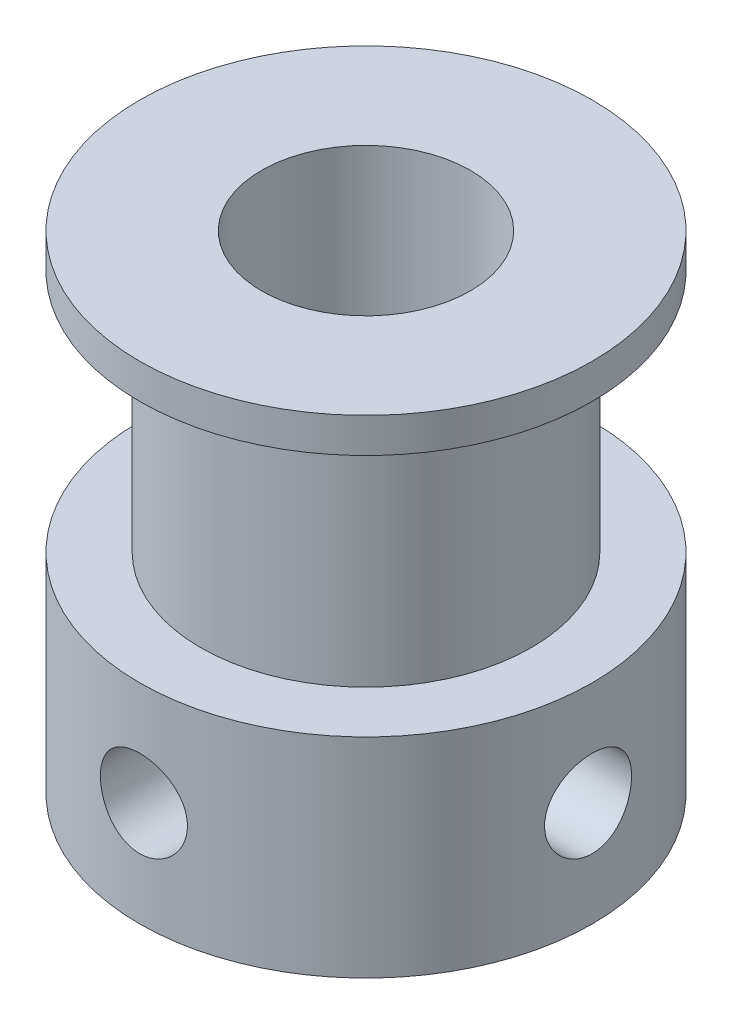
SolidWorks part; units mm, degrees
material "6063-O"
ref_plane "前视基准面" through (0, 0, 0) normal (0, 0, 1) x (1, 0, 0)
ref_plane "上视基准面" through (0, 0, 0) normal (0, 1, 0) x (1, 0, 0)
ref_plane "右视基准面" through (0, 0, 0) normal (1, 0, 0) x (0, 0, -1)
sketch "草图1" plane through (0, 0, 0) normal (0, 0, 1) x (1, 0, 0)
  line L0 (0, 0) -> (0, 14) construction
  line L1 (3, 0) -> (6.5, 0)
  line L2 (6.5, 0) -> (6.5, 6)
  line L3 (6.5, 6) -> (4.75, 6)
  line L4 (4.75, 6) -> (4.75, 13)
  line L5 (4.75, 13) -> (6.5, 13)
  line L6 (6.5, 13) -> (6.5, 14)
  line L7 (6.5, 14) -> (3, 14)
  line L8 (3, 14) -> (3, 0)
  dimension "D1" = 6
  dimension "D2" = 13
  dimension "D3" = 14
  dimension "D4" = 7
  dimension "D5" = 9.5
  dimension "D6" = 1
revolve "旋转1" add sketch "草图1" angle 360 about L0
hole_wizard "M3 螺纹孔1" positions "草图2" profile "草图3" tap size "M3" standard "GB"
sketch "草图2" plane through (0, 0, 0) normal (0, 0, 1) x (1, 0, 0)
  point P0 (0, 3)
  dimension "D1" = 3
sketch "草图3" plane through (0, 3, 0) normal (1, 0, 0) x (0, 1, 0)
  line L0 (0, 0) -> (0, 6.5)
  line L1 (0, 6.5) -> (1.25, 6.5)
  line L2 (1.25, 6.5) -> (1.25, 0.275)
  line L3 (1.25, 0.275) -> (1.525, 0)
  line L5 (1.525, 0) -> (0, 0)
  line L6 (-1.25, 0.275) -> (-1.525, 0) construction
  line L11 (0, -6.35) -> (0, 107.95) construction
  dimension "通孔螺纹孔钻头直径" = 2.5
  dimension "通孔螺纹孔钻头深度" = 6.5
  dimension "近端锥形沉头孔直径" = 3.05
  dimension "近端锥形沉头孔角度" = 90
cosmetic thread "孔螺蚊线1" parameters "D2"=3
hole_wizard "M3 螺纹孔2" positions "草图4" profile "草图5" tap size "M3" standard "GB"
sketch "草图4" plane through (0, 0, 0) normal (1, 0, 0) x (0, 0, -1)
  point P0 (0, 3)
  dimension "D1" = 3
sketch "草图5" plane through (0, 3, 0) normal (0, 1, 0) x (0, 0, 1)
  line L0 (0, 0) -> (0, 6.5)
  line L1 (0, 6.5) -> (1.25, 6.5)
  line L2 (1.25, 6.5) -> (1.25, 0.275)
  line L3 (1.25, 0.275) -> (1.525, 0)
  line L5 (1.525, 0) -> (0, 0)
  line L6 (-1.25, 0.275) -> (-1.525, 0) construction
  line L11 (0, -6.35) -> (0, 107.95) construction
  dimension "通孔螺纹孔钻头直径" = 2.5
  dimension "通孔螺纹孔钻头深度" = 6.5
  dimension "近端锥形沉头孔直径" = 3.05
  dimension "近端锥形沉头孔角度" = 90
cosmetic thread "孔螺蚊线2" parameters "D2"=3
